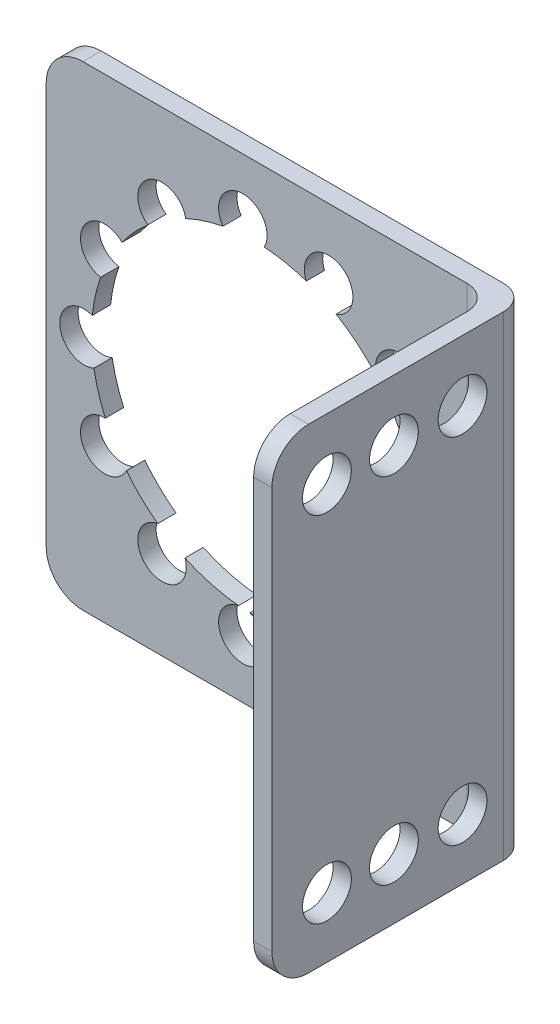
SolidWorks part; units mm, degrees
ref_plane "Front Plane" through (0, 0, 0) normal (0, 0, 1) x (1, 0, 0)
ref_plane "Top Plane" through (0, 0, 0) normal (0, 1, 0) x (1, 0, 0)
ref_plane "Right Plane" through (0, 0, 0) normal (1, 0, 0) x (0, 0, -1)
sketch "Sketch1" plane through (0, 0, 0) normal (0, 0, 1) x (1, 0, 0)
  line L0 (0, 23.4033) -> (0, -22.5712) construction
  line L1 (-38, 0) -> (38.0693, 0) construction
  line L3 (-19, 19.5) -> (19, 19.5)
  line L4 (-19, 19.5) -> (-19, -19.4507)
  line L5 (-19, -19.4507) -> (19, -19.4507)
  line L6 (19, 19.5) -> (19, -19.4507)
  circle A0 centre (-2, 0.5) radius 13.295
  dimension "D6" = 21
  dimension "D7" = 19
  dimension "D1" = 19
  dimension "D2" = 19
  dimension "D3" = 19.5
  dimension "D4" = 19.4507
  dimension "D5" = 17
extrude "Boss-Extrude1" add sketch "Sketch1" along normal blind 1.5
sketch "Sketch3" plane through (0, 0, 0) normal (1, 0, 0) x (0, 0, -1)
  line L0 (-1.5, -19.4507) -> (0, -19.4507) construction
  line L1 (-1.5, 19.5) -> (-21, 19.5)
  line L2 (-1.5, 19.5) -> (-1.5, -19.4507)
  line L3 (-1.5, -19.4507) -> (-21, -19.4507)
  line L4 (-21, 19.5) -> (-21, -19.4507)
  line L5 (6.7923, 14.5) -> (-30.3305, 14.5) construction
  line L6 (9.2467, -14.4507) -> (-32.5548, -14.4507) construction
  line L7 (-5.5, 22.6408) -> (-5.5, -29.9754) construction
  line L8 (-11, 25.0952) -> (-11, -30.8958) construction
  line L9 (-16.5, 25.0952) -> (-16.5, -30.4356) construction
  dimension "D1" = 19.5
  dimension "D2" = 0
  dimension "D3" = 5
  dimension "D4" = 5
  dimension "D5" = 4
  dimension "D6" = 5.5
  dimension "D7" = 5.5
ref_plane "Plane1" through (19, 0, 0) normal (1, 0, 0) x (0, 0, -1)
sketch "Sketch4" plane through (19, 0, 0) normal (1, 0, 0) x (0, 0, -1)
  line L1 (-1.5, 19.5) -> (-21, 19.5)
  line L2 (-1.5, 19.5) -> (-1.5, -19.4507)
  line L3 (-1.5, -19.4507) -> (-21, -19.4507)
  line L4 (-21, 19.5) -> (-21, -19.4507)
extrude "Boss-Extrude2" add sketch "Sketch4" against normal blind 1.5
sketch "Sketch5" plane through (0, 0, 0) normal (1, 0, 0) x (0, 0, -1)
  line L0 (6.7923, 14.5) -> (-30.3305, 14.5) construction
  line L1 (-11, 25.0952) -> (-11, -30.8958) construction
  line L2 (19.8179, 0) -> (-38.0004, 0) construction
  circle A0 centre (-5.3757, 14.5) radius 2
  circle A1 centre (-11, 14.5) radius 2
  circle A2 centre (-16.4922, 14.5) radius 2
  circle A3 centre (-16.4922, -14.5) radius 2
  circle A4 centre (-11, -14.5) radius 2
  circle A5 centre (-5.3757, -14.5) radius 2
extrude "Cut-Extrude2" cut sketch "Sketch5" against normal through all both and the other way through all
fillet "Fillet2" radius 3 4 edges at (18.25, -19.4507, 21) (18.25, 19.5, 21) (-19, -19.4507, 0.75) (-19, 19.5, 0.75)
fillet "Fillet6" radius 2 2 edges at (19, 0.0246, 0)
sketch "Sketch6" plane through (0, 0, 0) normal (0, 0, 1) x (1, 0, 0)
  line L0 (42.0849, 0) -> (-41.1874, 0) construction
  circle A0 centre (-15.9, 0) radius 1.9867
  circle A1 centre (-14.2047, 6.8779) radius 1.9867
  circle A2 centre (-9.5074, 12.1802) radius 1.9867
  circle A3 centre (-2.8839, 14.6921) radius 1.9867
  circle A4 centre (4.1482, 13.8382) radius 1.9867
  circle A5 centre (9.978, 9.8142) radius 1.9867
  circle A6 centre (13.2699, 3.5419) radius 1.9867
  circle A7 centre (13.2699, -3.5419) radius 1.9867
  circle A8 centre (9.978, -9.8142) radius 1.9867
  circle A9 centre (4.1482, -13.8382) radius 1.9867
  circle A10 centre (-2.8839, -14.6921) radius 1.9867
  circle A11 centre (-9.5074, -12.1802) radius 1.9867
  circle A12 centre (-14.2047, -6.8779) radius 1.9867
  point P32 (-1.1, 0)
  dimension "D1" = 13
extrude "Cut-Extrude5" cut sketch "Sketch6" along normal up to surface (1.5 mm away) up to face at (11.295, 0.5, 1.5)
